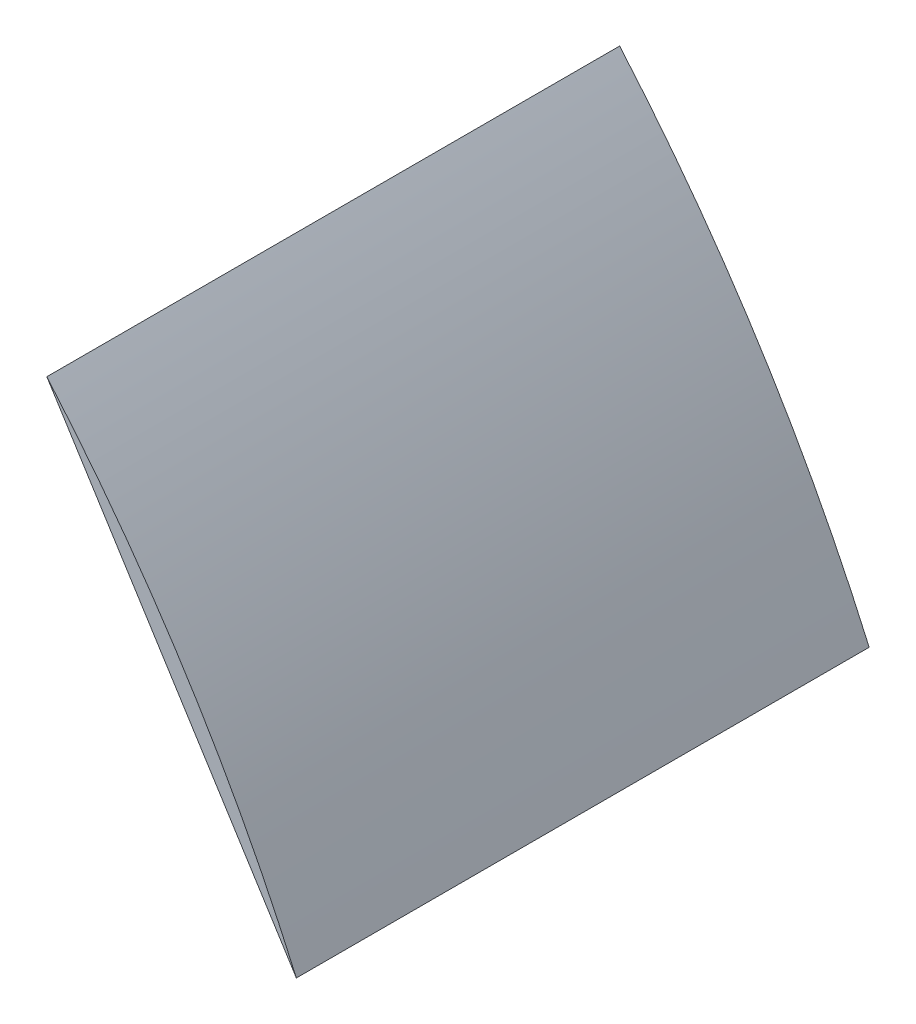
SolidWorks part; units mm, degrees
ref_plane "Front Plane" through (0, 0, 0) normal (0, 0, 1) x (1, 0, 0)
ref_plane "Top Plane" through (0, 0, 0) normal (0, 1, 0) x (1, 0, 0)
ref_plane "Right Plane" through (0, 0, 0) normal (1, 0, 0) x (0, 0, -1)
sketch "CurveSketch" plane through (0, 0, 0) normal (0, 0, 1) x (1, 0, 0)
  line L0 (9.8175, 26.5905) -> (12.9273, 21.6558)
  arc A0 (12.9273, 21.6558) -> (9.8175, 26.5905) centre (-5.137, 13.719) ccw
  dimension "D1" = 19.731
extrude "CurveBoss" add sketch "CurveSketch" along normal blind 7.139
